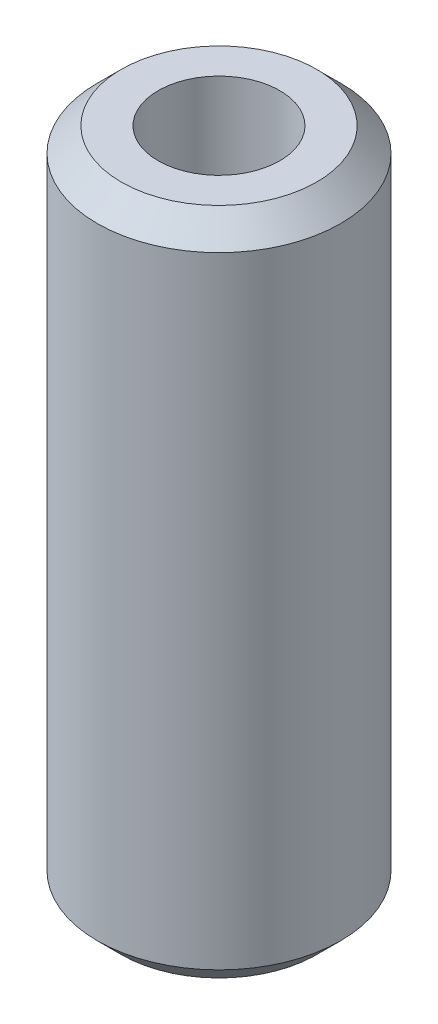
SolidWorks part; units mm, degrees
ref_plane "Front Plane" through (0, 0, 0) normal (0, 0, 1) x (1, 0, 0)
ref_plane "Top Plane" through (0, 0, 0) normal (0, 1, 0) x (1, 0, 0)
ref_plane "Right Plane" through (0, 0, 0) normal (1, 0, 0) x (0, 0, -1)
sketch "Sketch1" plane through (0, 0, 0) normal (0, 1, 0) x (1, 0, 0)
  circle A0 centre (0, 0) radius 6.35
  circle A1 centre (0, 0) radius 12.7
  dimension "D1" = 12.7
  dimension "D2" = 25.4
extrude "Boss-Extrude1" add sketch "Sketch1" along normal blind 69.85
chamfer "Chamfer1" distance 2.5 angle 45 2 edges at (0, 0, 12.7) (0, 69.85, 12.7)
